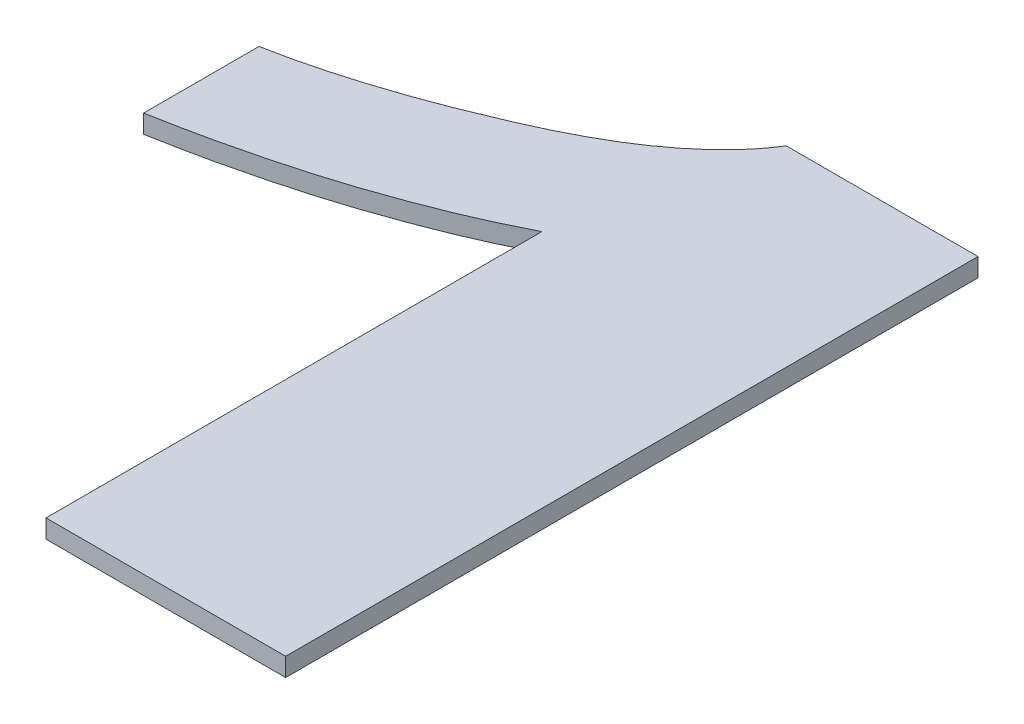
SolidWorks part; units mm, degrees
material "PET"
ref_plane "Alzado" through (0, 0, 0) normal (0, 0, 1) x (1, 0, 0)
ref_plane "Planta" through (0, 0, 0) normal (0, 1, 0) x (1, 0, 0)
ref_plane "Vista lateral" through (0, 0, 0) normal (1, 0, 0) x (0, 0, -1)
sketch "Croquis1" plane through (0, 0, 0) normal (0, 1, 0) x (1, 0, 0)
  line L0 (-26.7827, 0) -> (33.762, 0) construction
  text T0 "1" height 30
extrude "Saliente-Extruir1" add sketch "Croquis1" along normal blind 0.8
